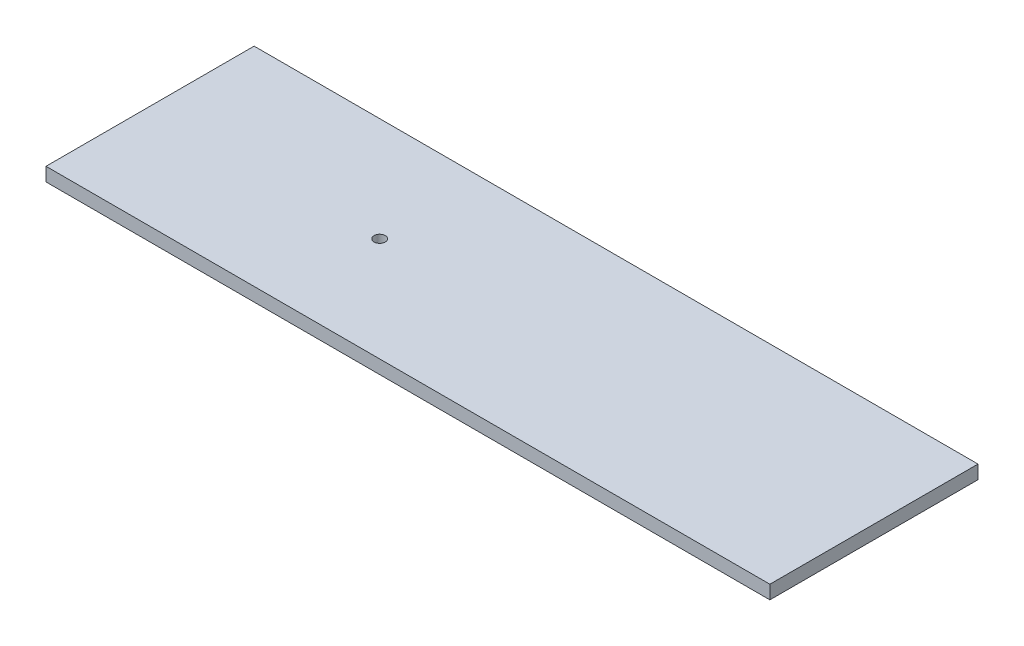
SolidWorks part; units mm, degrees
ref_plane "Front Plane" through (0, 0, 0) normal (0, 0, 1) x (1, 0, 0)
ref_plane "Top Plane" through (0, 0, 0) normal (0, 1, 0) x (1, 0, 0)
ref_plane "Right Plane" through (0, 0, 0) normal (1, 0, 0) x (0, 0, -1)
sketch "Sketch1" plane through (0, 0, 0) normal (0, 1, 0) x (1, 0, 0)
  line L0 (-20, 5.75) -> (20, -5.75) construction
  line L1 (-20, 5.75) -> (20, 5.75)
  line L2 (-20, 5.75) -> (-20, -5.75)
  line L3 (-20, -5.75) -> (20, -5.75)
  line L4 (20, 5.75) -> (20, -5.75)
  line L5 (20, 5.75) -> (-20, -5.75) construction
  dimension "D1" = 40
  dimension "D2" = 11.5
extrude "Boss-Extrude1" add sketch "Sketch1" along normal mid plane 0.75
scale "Scale1" scale about centroid uniform scaling yes scale factor 10
sketch "Sketch2" plane through (0, 3.75, 0) normal (0, 1, 0) x (1, 0, 0)
  line L0 (-200, 0) -> (-73.1, 0)
  line L1 (-200, 57.5) -> (-200, -57.5) construction
  circle A0 centre (-73.1, 0) radius 3.1
extrude "Cut-Extrude1" cut sketch "Sketch2" against normal through all
